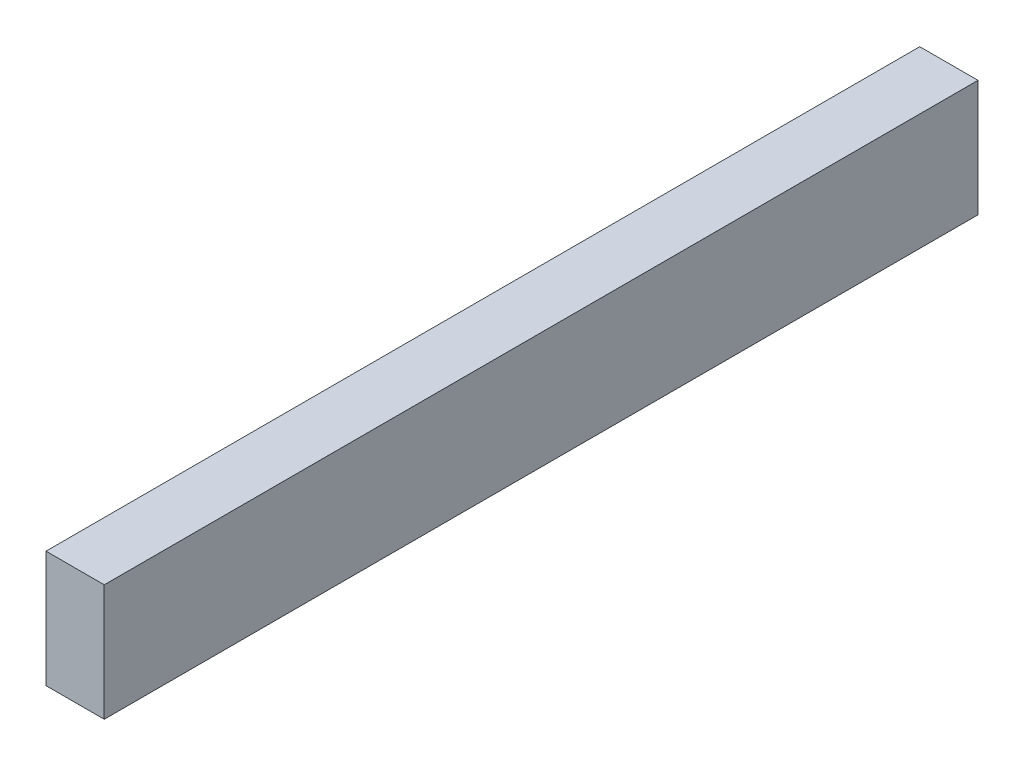
SolidWorks part; units mm, degrees
ref_plane "Front Plane" through (0, 0, 0) normal (0, 0, 1) x (1, 0, 0)
ref_plane "Top Plane" through (0, 0, 0) normal (0, 1, 0) x (1, 0, 0)
ref_plane "Right Plane" through (0, 0, 0) normal (1, 0, 0) x (0, 0, -1)
sketch "Sketch1" plane through (0, 0, 0) normal (0, 0, 1) x (1, 0, 0)
  line L1 (0, 0) -> (25.4, 0)
  line L2 (0, 0) -> (0, 50.8)
  line L3 (0, 50.8) -> (25.4, 50.8)
  line L4 (25.4, 0) -> (25.4, 50.8)
  dimension "D1" = 50.8
  dimension "D2" = 25.4
extrude "Boss-Extrude1" add sketch "Sketch1" along normal blind 381
